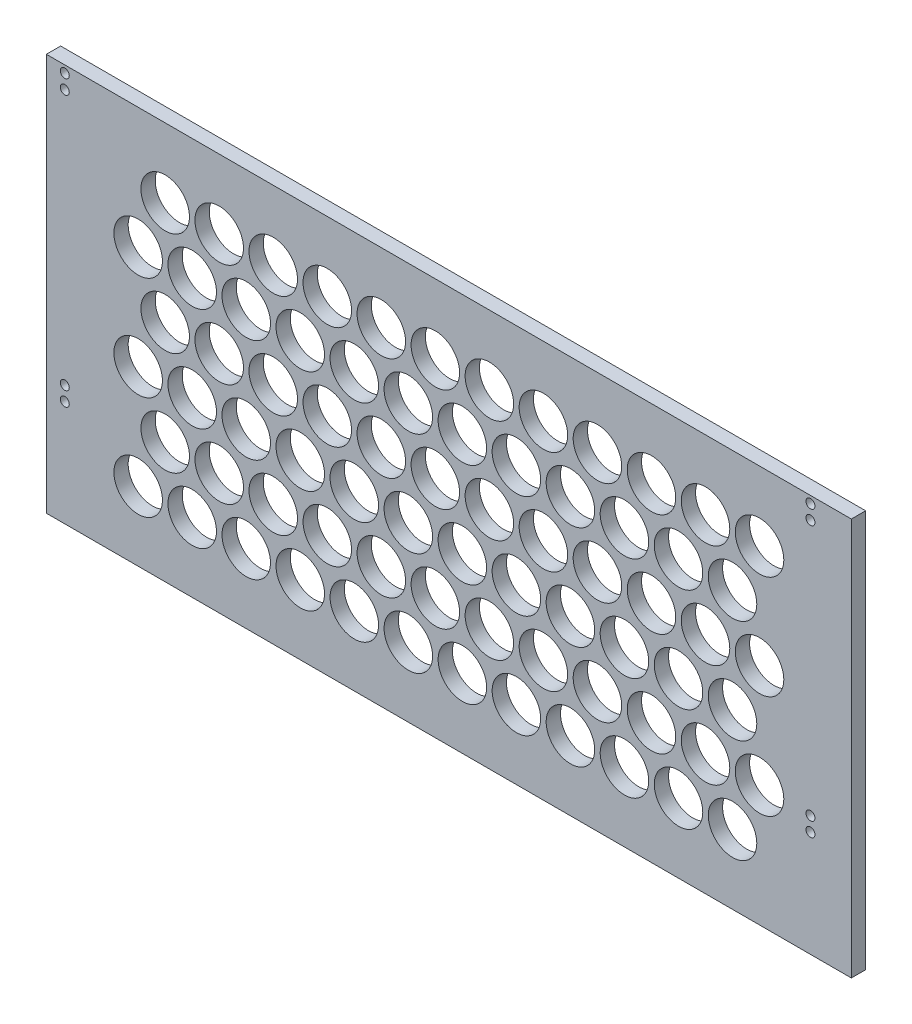
SolidWorks part; units mm, degrees
material "ABS"
ref_plane "X-Y Datum" through (0, 0, 0) normal (0, 0, 1) x (1, 0, 0)
ref_plane "X-Z Datum" through (0, 0, 0) normal (0, 1, 0) x (1, 0, 0)
ref_plane "Y-Z Datum" through (0, 0, 0) normal (1, 0, 0) x (0, 0, -1)
sketch "Sketch1" plane through (0, 0, 0) normal (0, 0, 1) x (1, 0, 0)
  line L1 (-148.775, 68.275) -> (148.775, 68.275)
  line L2 (-148.775, 68.275) -> (-148.775, -68.275)
  line L3 (-148.775, -68.275) -> (148.775, -68.275)
  line L4 (148.775, 68.275) -> (148.775, -68.275)
  line L5 (-148.775, 68.275) -> (148.775, -68.275) construction
  line L6 (-148.775, -68.275) -> (148.775, 68.275) construction
  line L13 (-178.775, -88.275) -> (178.775, -88.275)
  line L14 (-178.775, 88.275) -> (178.775, 88.275)
  line L15 (-178.775, 88.275) -> (-178.775, -88.275)
  line L16 (178.775, 88.275) -> (178.775, -88.275)
  line L17 (178.775, 68.275) -> (178.775, -68.275) construction
  line L18 (-148.775, 88.275) -> (148.775, 88.275) construction
  line L19 (-148.775, -88.275) -> (148.775, -88.275) construction
  line L20 (-178.775, 68.275) -> (-178.775, -68.275) construction
  circle A0 centre (-138, -57.5) radius 10.775
  circle A1 centre (-114, -57.5) radius 10.775 construction
  circle A2 centre (-126, -34.5) radius 10.775
  point P0 (0, 0)
  point P16 (178.775, -68.275)
  point P17 (-178.775, 75.4363)
  point P18 (0, 0)
  point P20 (0, 0)
  point P21 (178.775, 81.2149)
  point P22 (178.775, 81.7561)
  point P23 (178.775, 83.275)
  point P26 (178.775, 84.3617)
  point P27 (176.9313, -83.275)
  point P30 (178.775, -68.275)
  point P31 (178.775, -68.275)
  point P32 (178.775, -83.275)
  point P33 (-178.775, -83.275)
  point P34 (-178.775, -81.528)
  point P37 (-178.775, 83.275)
  point P38 (-178.775, 81.6344)
  point P39 (178.775, -68.275)
  point P40 (178.775, -81.6704)
  dimension "D1" = 21.55
  dimension "D2" = 24
  dimension "D3" = 23
  dimension "D4" = 12
  dimension "D5" = 136.55
  dimension "D6" = 297.55
  dimension "D7" = 20
  dimension "D8" = 20
  dimension "D9" = 30
  dimension "D10" = 30
extrude "Boss-Extrude1" add sketch "Sketch1" along normal blind 6.35
sketch "Sketch3" plane through (0, 0, 6.35) normal (0, 0, 1) x (1, 0, 0)
  line L4 (148.775, 68.275) -> (-148.775, 68.275)
  line L5 (148.775, -68.275) -> (148.775, 68.275)
  line L6 (-148.775, -68.275) -> (148.775, -68.275)
  line L7 (-148.775, 68.275) -> (-148.775, -68.275)
  line L8 (148.775, 68.275) -> (-148.775, 68.275)
  line L9 (148.775, -68.275) -> (148.775, 68.275)
  line L10 (-148.775, -68.275) -> (148.775, -68.275)
  line L11 (-148.775, 68.275) -> (-148.775, -68.275)
  circle A1 centre (-126, -34.5) radius 10.775
  circle A2 centre (-126, -34.5) radius 10.775
  circle A3 centre (-138, -57.5) radius 10.775
  circle A4 centre (-138, -57.5) radius 10.775
  dimension "D1" = 0
  dimension "D2" = 0
  dimension "D3" = 0
extrude "Cut-Extrude1" cut sketch "Sketch3" against normal through all contours A4
sketch "Sketch4" plane through (0, 0, 6.35) normal (0, 0, 1) x (1, 0, 0)
  line L4 (148.775, 68.275) -> (-148.775, 68.275)
  line L5 (148.775, -68.275) -> (148.775, 68.275)
  line L6 (-148.775, -68.275) -> (148.775, -68.275)
  line L7 (-148.775, 68.275) -> (-148.775, -68.275)
  line L8 (148.775, 68.275) -> (-148.775, 68.275)
  line L9 (148.775, -68.275) -> (148.775, 68.275)
  line L10 (-148.775, -68.275) -> (148.775, -68.275)
  line L11 (-148.775, 68.275) -> (-148.775, -68.275)
  circle A1 centre (-126, -34.5) radius 10.775
  circle A2 centre (-126, -34.5) radius 10.775
  circle A3 centre (-138, -57.5) radius 10.775
  circle A4 centre (-138, -57.5) radius 10.775
  dimension "D1" = 0
  dimension "D2" = 0
  dimension "D3" = 0
extrude "Cut-Extrude2" cut sketch "Sketch4" against normal through all contours A2
pattern_linear "LPattern1" count 12 spacing 24 along (1, 0, 0) of "Cut-Extrude1", "Cut-Extrude2"
pattern_linear "LPattern2" count 3 spacing 46 along (0, 1, 0) of "LPattern1", "Cut-Extrude1", "Cut-Extrude2"
sketch "Sketch5" plane through (0, 0, 0) normal (0, 0, -1) x (-1, 0, 0)
  circle A0 centre (170.6, 85.1) radius 2 construction
  circle A1 centre (170.6, 78.75) radius 2 construction
  circle A2 centre (170.6, -34.9) radius 2 construction
  circle A3 centre (170.6, -41.25) radius 2 construction
  circle A4 centre (-160.6, 85.1) radius 2 construction
  circle A5 centre (-160.6, 78.75) radius 2 construction
  circle A6 centre (-160.6, -34.9) radius 2 construction
  circle A7 centre (-160.6, -41.25) radius 2 construction
  circle A8 centre (170.6, 85.1) radius 2
  circle A9 centre (170.6, 78.75) radius 2
  circle A10 centre (170.6, -34.9) radius 2
  circle A11 centre (170.6, -41.25) radius 2
  circle A12 centre (-160.6, 85.1) radius 2
  circle A13 centre (-160.6, 78.75) radius 2
  circle A14 centre (-160.6, -34.9) radius 2
  circle A15 centre (-160.6, -41.25) radius 2
extrude "Cut-Extrude3" cut sketch "Sketch5" against normal through all
